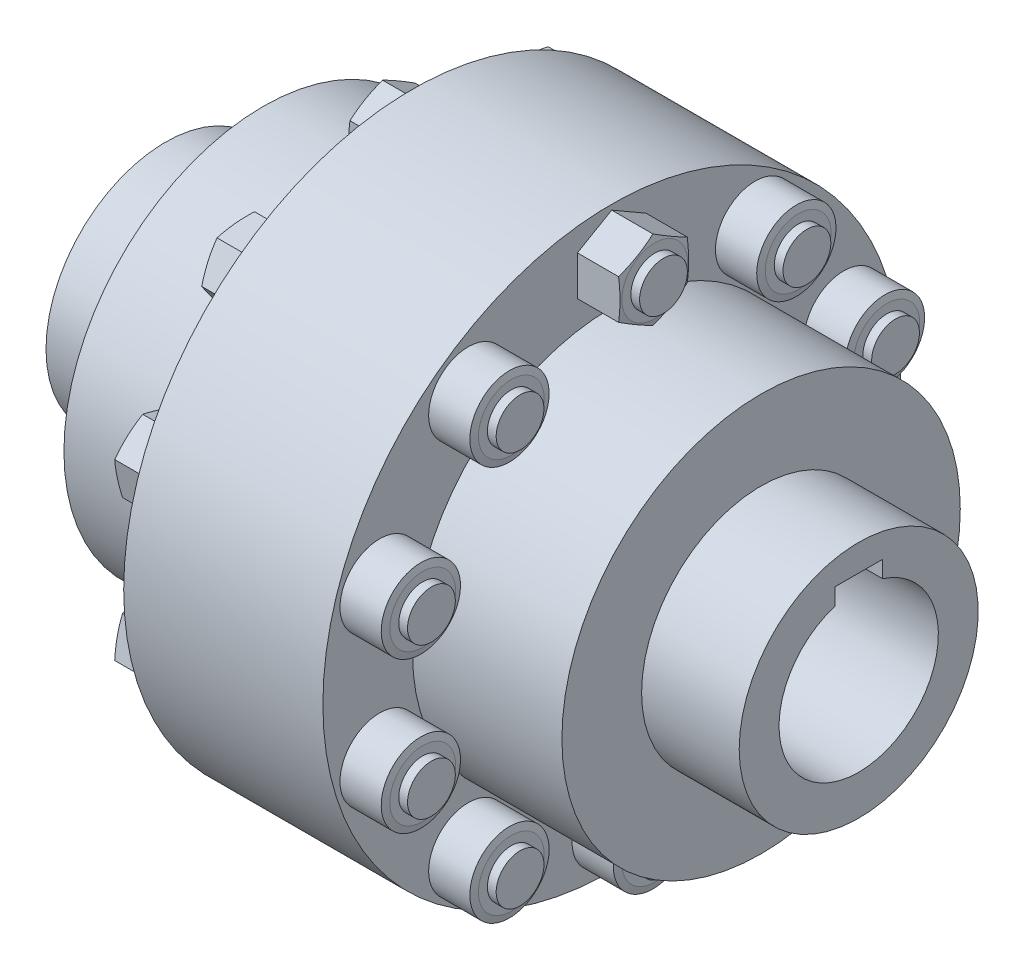
SolidWorks part; units mm, degrees
ref_plane "Спереди" through (0, 0, 0) normal (0, 0, 1) x (1, 0, 0)
ref_plane "Сверху" through (0, 0, 0) normal (0, 1, 0) x (1, 0, 0)
ref_plane "Справа" through (0, 0, 0) normal (1, 0, 0) x (0, 0, -1)
sketch "Эскиз1" plane through (0, 0, 0) normal (0, 0, 1) x (1, 0, 0)
  line L0 (-87, 20) -> (-87, 30)
  line L1 (-87, 30) -> (-62.5, 30)
  line L2 (-62.5, 30) -> (-62.5, 50)
  line L3 (-62.5, 50) -> (-25, 50)
  line L4 (62.5, 50) -> (62.5, 30)
  line L5 (25, 72.5) -> (25, 50)
  line L6 (25, 72.5) -> (-25, 72.5)
  line L7 (-25, 72.5) -> (-25, 50)
  line L8 (25, 50) -> (62.5, 50)
  line L9 (62.5, 30) -> (87, 30)
  line L10 (87, 30) -> (87, 20)
  line L12 (-5, 30) -> (-5, 20)
  line L15 (5, 30) -> (5, 20)
  line L16 (-87, 20) -> (-5, 20)
  line L18 (-98.6071, 0) -> (92.8961, 0) construction
  line L25 (5, 20) -> (87, 20)
  line L31 (0, 72.5) -> (0, -98.3961) construction
  line L34 (-5, 30) -> (-24, 30)
  line L35 (-24, 30) -> (-24, 45)
  line L36 (-24, 45) -> (24, 45)
  line L37 (24, 45) -> (24, 30)
  line L38 (-5, 20) -> (0, 20) construction
  line L39 (0, 20) -> (5, 20) construction
  line L40 (24, 30) -> (5, 30)
  line L41 (-61.5, 45) -> (-61.5, 30)
  line L42 (-61.5, 30) -> (-36, 30)
  line L45 (36, 45) -> (61.5, 45)
  line L46 (61.5, 45) -> (61.5, 30)
  line L47 (61.5, 30) -> (36, 30)
  line L48 (36, 30) -> (36, 45)
  line L49 (-61.5, 45) -> (-36, 45)
  line L50 (-61.5, 45) -> (-62.5, 45) construction
  line L51 (24, 45) -> (36, 45) construction
  line L52 (61.5, 45) -> (62.5, 45) construction
  line L53 (-36, 45) -> (-36, 30)
  line L54 (-24, 45) -> (-36, 45) construction
  line L55 (-61.5, 45) -> (-61.5, 50) construction
  line L56 (61.5, 50) -> (61.5, 45) construction
  point P27 (-30, 45)
  point P32 (30, 45)
  dimension "D" = 145
  dimension "dmin" = 40
  dimension "D2" = 60
  dimension "D1" = 100
  dimension "lmin" = 82
  dimension "B" = 50
  dimension "L" = 174
  dimension "bmin" = 12
  dimension "A" = 60
  dimension "lminPol" = 125
  dimension "TolKr" = 1
  dimension "TM" = 5
revolve "Повернуть1" add sketch "Эскиз1" angle 360 about L18
sketch "Эскиз3" plane through (0, 0, 0) normal (1, 0, 0) x (0, 0, -1)
  line L1 (-6, 0) -> (6, 0)
  line L2 (-6, 0) -> (-6, 23.3)
  line L3 (-6, 23.3) -> (6, 23.3)
  line L4 (6, 0) -> (6, 23.3)
  point P4 (0, 0)
  dimension "Bshpon" = 12
  dimension "Dplust2shpon" = 23.3
extrude "Вырез-Вытянуть1" cut sketch "Эскиз3" against normal through all both and the other way through all
sketch "Эскиз2" plane through (0, 0, 0) normal (0, 0, 1) x (1, 0, 0)
  line L0 (-33, 61.25) -> (38, 61.25)
  line L1 (35.8, 67.25) -> (35.8, 69.5)
  line L2 (35.3445, 71.2) -> (25, 71.2)
  line L3 (25, -72.5) -> (25, 72.5) construction
  line L4 (25, 71.2) -> (25, 67.25)
  line L6 (-25, 72.5) -> (-25, -72.5) construction
  line L7 (-33, 68.9) -> (-33, 61.25)
  line L8 (-25, 70.7) -> (-25, 67.25)
  line L9 (-25, 67.25) -> (25, 67.25)
  line L10 (-33, 61.25) -> (48.3147, 61.25) construction
  line L11 (-32.5177, 70.7) -> (-25, 70.7)
  line L12 (35.8, 67.25) -> (38, 67.25)
  line L13 (38, 67.25) -> (38, 61.25)
  line L15 (0, 0) -> (45.6917, 0) construction
  line L16 (-32.5177, 70.7) -> (-33, 68.9)
  line L17 (35.3445, 71.2) -> (35.8, 69.5)
  point P3 (36.0049, 69.2905)
  point P8 (0, 0)
  point P17 (-25, 68.975)
  dimension "d1minB" = 12
  dimension "eminG" = 19.9
  dimension "eminB" = 18.9
  dimension "lminB" = 63
  dimension "DB" = 122.5
  dimension "kminB" = 8
  dimension "kminG" = 10.8
  dimension "D4" = 15
  dimension "D5" = 15
  dimension "Dbolt" = 15.3
  dimension "DG" = 16.5
revolve "Повернуть2" add sketch "Эскиз2" angle 360 about L0
sketch "Эскиз5" plane through (-33, 0, 0) normal (-1, 0, 0) x (0, 0, 1)
  line L1 (0, 70.7) -> (-8.1839, 65.975)
  line L2 (-8.1839, 65.975) -> (-8.1839, 56.525)
  line L3 (-8.1839, 56.525) -> (0, 51.8)
  line L4 (0, 51.8) -> (8.1839, 56.525)
  line L5 (8.1839, 56.525) -> (8.1839, 65.975)
  line L6 (8.1839, 65.975) -> (0, 70.7)
  circle A0 centre (0, 61.25) radius 8.1839 construction
  circle A1 centre (0, 61.25) radius 9.45
extrude "Вырез-Вытянуть2" cut sketch "Эскиз5" against normal up to surface (8 mm away) contours L1 A1 | L6 A1 | L2 A1 | L3 A1 | L4 A1 | L5 A1 up to face at (-25, 61.25, -9.45)
sketch "Эскиз6" plane through (35.8, 0, 0) normal (1, 0, 0) x (0, 0, -1)
  line L1 (0, 71.2) -> (-8.617, 66.225)
  line L2 (-8.617, 66.225) -> (-8.617, 56.275)
  line L3 (-8.617, 56.275) -> (0, 51.3)
  line L4 (0, 51.3) -> (8.617, 56.275)
  line L5 (8.617, 56.275) -> (8.617, 66.225)
  line L6 (8.617, 66.225) -> (0, 71.2)
  circle A0 centre (0, 61.25) radius 8.617 construction
  circle A1 centre (0, 61.25) radius 9.95
extrude "Вырез-Вытянуть3" cut sketch "Эскиз6" against normal up to surface (10.8 mm away) contours L1 A1 | L6 A1 | L2 A1 | L3 A1 | L4 A1 | L5 A1 up to face at (25, 61.25, 9.95)
pattern_circular "Круговой массив1" count 10 over 360 about axis through (0, 0, 0) along (1, 0, 0) of "Повернуть2", "Вырез-Вытянуть2"
equation "\"DB\"= ( ( \"D@Эскиз1\" - \"D1@Эскиз1\" ) / 2 ) + \"D1@Эскиз1\""
equation "\"DB@Эскиз2\"=\"DB\""
equation "\"Толщина муфты\"= ( \"D2@Эскиз1\" - \"dmin@Эскиз1\" ) / 4"
equation "\"TM@Эскиз1\"=\"Толщина муфты\""
